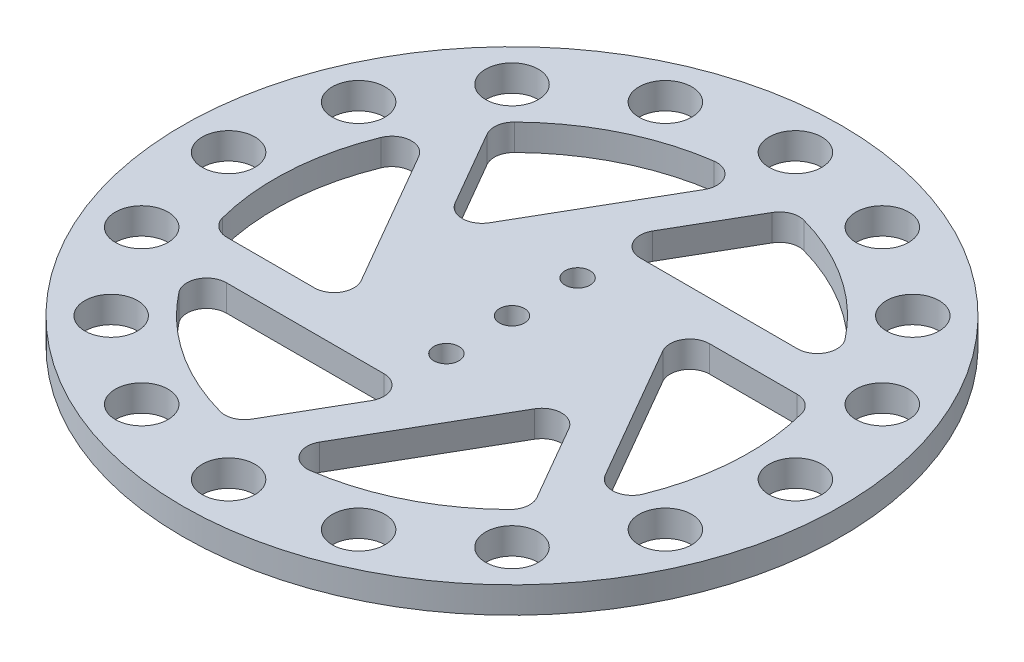
SolidWorks part; units mm, degrees
ref_plane "Front Plane" through (0, 0, 0) normal (0, 0, 1) x (1, 0, 0)
ref_plane "Top Plane" through (0, 0, 0) normal (0, 1, 0) x (1, 0, 0)
ref_plane "Right Plane" through (0, 0, 0) normal (1, 0, 0) x (0, 0, -1)
sketch "Sketch1" plane through (0, 0, 0) normal (0, 1, 0) x (1, 0, 0)
  circle A0 centre (0, 0) radius 50
  dimension "D1" = 100
extrude "Boss-Extrude1" add sketch "Sketch1" along normal blind 4
sketch "Sketch2" plane through (0, 4, 0) normal (0, 1, 0) x (1, 0, 0)
  circle A0 centre (0, 0) radius 43 construction
  circle A1 centre (0, 43) radius 4
  circle A2 centre (0, 0) radius 50 construction
  dimension "D1" = 8
  dimension "D2" = 7
extrude "Cut-Extrude1" cut sketch "Sketch2" against normal up to surface (4 mm away) up to face at (0, 0, 50)
pattern_circular "CirPattern1" count 16 over 360 about axis through (0, 0, 0) along (0, 1, 0) of "Cut-Extrude1"
sketch "Sketch3" plane through (0, 4, 0) normal (0, 1, 0) x (1, 0, 0)
  line L0 (10, 17.3205) -> (31.5595, 17.3205)
  line L1 (6.5359, 11.3205) -> (-6.5359, 11.3205)
  line L2 (-6.5359, 11.3205) -> (-13.0718, 0)
  line L3 (-13.0718, 0) -> (-6.5359, -11.3205)
  line L4 (-6.5359, -11.3205) -> (6.5359, -11.3205)
  line L5 (6.5359, -11.3205) -> (13.0718, 0)
  line L6 (13.0718, 0) -> (6.5359, 11.3205)
  line L7 (10, 17.3205) -> (-10, 17.3205)
  line L8 (-10, 17.3205) -> (-20, 0)
  line L9 (-20, 0) -> (-10, -17.3205)
  line L10 (-10, -17.3205) -> (10, -17.3205)
  line L11 (10, -17.3205) -> (20, 0)
  line L12 (20, 0) -> (10, 17.3205)
  line L14 (-6.5359, 11.3205) -> (7.283, 35.2556)
  circle A2 centre (0, 0) radius 11.3205 construction
  circle A3 centre (0, 0) radius 17.3205 construction
  circle A4 centre (0, 0) radius 36
  arc A5 (-0.4737, 21.8205) -> (2.1244, 17.3205) centre (2.1244, 20.3205) ccw
  circle A6 centre (0, 0) radius 50 construction
  arc A7 (9.5576, 34.7081) -> (6.1631, 33.3158) centre (8.7611, 31.8158) ccw
  arc A8 (26.0015, 17.3205) -> (28.3653, 22.1678) centre (26.0015, 20.3205) ccw
  dimension "D1" = 14
  dimension "D4" = 6
  dimension "D2" = 6
  dimension "D3" = 20
extrude "Cut-Extrude2" cut sketch "Sketch3" against normal up to surface (4 mm away)
pattern_circular "CirPattern3" count 6 over 360 about axis through (0, 0, 0) along (0, 1, 0) of "Cut-Extrude2"
sketch "Sketch5" plane through (0, 4, 0) normal (0, 1, 0) x (1, 0, 0)
  line L0 (0, -9.95) -> (0, 9.95) construction
  circle A1 centre (0, 9.95) radius 1.9
  circle A2 centre (0, 0) radius 1.9
  circle A3 centre (0, -9.95) radius 1.9
  point P3 (0, 0)
  dimension "D1" = 3.8
  dimension "D2" = 19.9
extrude "Cut-Extrude3" cut sketch "Sketch5" against normal up to surface (4 mm away) up to face at (15.1945, 0, 22.7686)
